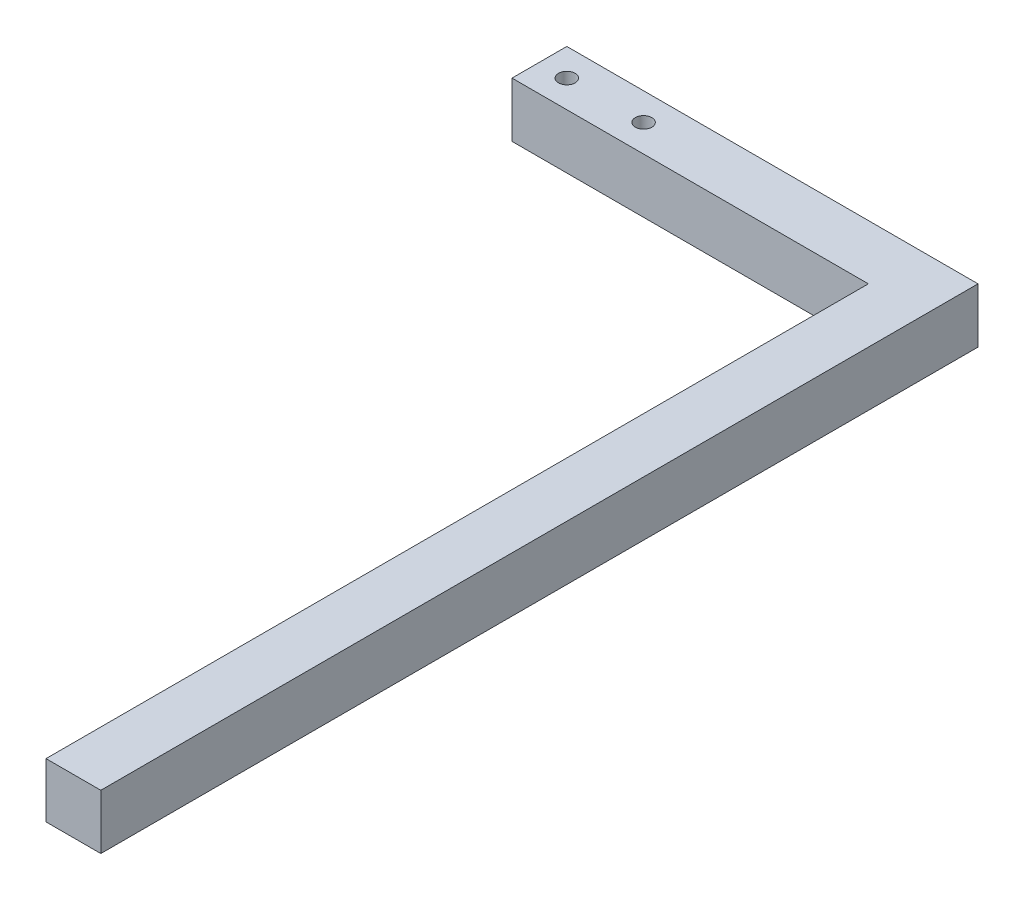
SolidWorks part; units mm, degrees
material "50%PLA"
ref_plane "Front Plane" through (0, 0, 0) normal (0, 0, 1) x (1, 0, 0)
ref_plane "Top Plane" through (0, 0, 0) normal (0, 1, 0) x (1, 0, 0)
ref_plane "Right Plane" through (0, 0, 0) normal (1, 0, 0) x (0, 0, -1)
sketch "Sketch1" plane through (0, 0, 0) normal (0, 1, 0) x (1, 0, 0)
  line L0 (0, 10) -> (75, 10)
  line L1 (0, 0) -> (75, 0)
  line L2 (0, 0) -> (0, 10)
  line L9 (75, 10) -> (75, 0)
  circle A0 centre (5, 5) radius 1.5183
  circle A1 centre (19, 5) radius 1.5183
  dimension "D1" = 10
  dimension "D2" = 75
  dimension "D3" = 10
  dimension "D6" = 14
  dimension "D7" = 5
  dimension "D8" = 5
extrude "Boss-Extrude1" add sketch "Sketch1" along normal blind 10
sketch "Sketch5" plane through (0, 0, 0) normal (0, 0, 1) x (1, 0, 0)
  line L0 (0, 10) -> (75, 10) construction
  line L1 (75, 0) -> (65, 0)
  line L2 (75, 0) -> (75, 10)
  line L3 (75, 10) -> (65, 10)
  line L4 (65, 0) -> (65, 10)
  dimension "D1" = 10
extrude "Boss-Extrude3" add sketch "Sketch5" along normal blind 150
